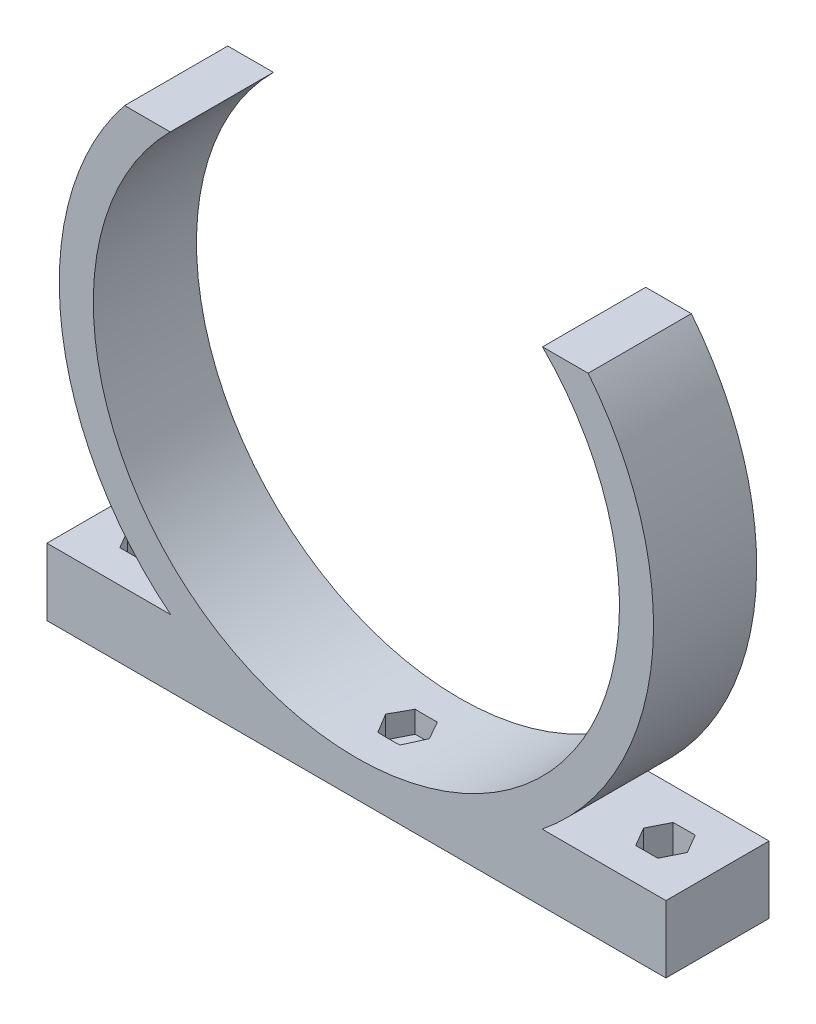
SolidWorks part; units mm, degrees
material "PE High Density"
ref_plane "Front Plane" through (0, 0, 0) normal (0, 0, 1) x (1, 0, 0)
ref_plane "Top Plane" through (0, 0, 0) normal (0, 1, 0) x (1, 0, 0)
ref_plane "Right Plane" through (0, 0, 0) normal (1, 0, 0) x (0, 0, -1)
sketch "Sketch2" plane through (0, 0, 0) normal (0, 0, 1) x (1, 0, 0)
  line L0 (0, 0) -> (38.1, 0)
  line L1 (0, 0) -> (-38.1, 0)
  line L2 (-38.1, 0) -> (-38.1, 8.255)
  line L3 (38.1, 0) -> (38.1, 8.255)
  line L4 (38.1, 8.255) -> (22.86, 8.255)
  line L5 (-38.1, 8.255) -> (-22.8663, 8.255)
  line L6 (-28.5349, 59.69) -> (-22.9171, 59.69)
  line L7 (22.9107, 59.69) -> (28.5286, 59.69)
  arc A2 (-28.5349, 59.69) -> (-22.8663, 8.255) centre (-0.0032, 36.8046) ccw
  arc A3 (-22.9171, 59.69) -> (22.9107, 59.69) centre (-0.0032, 36.8046) ccw
  arc A4 (22.86, 8.255) -> (28.5286, 59.69) centre (-0.0032, 36.8046) ccw
  point P10 (0, 0)
  dimension "D7" = 4.191
  dimension "D8" = 64.77
  dimension "D9" = 4.4196
  dimension "D1" = 38.1
  dimension "D2" = 38.1
  dimension "D3" = 8.255
  dimension "D4" = 8.255
  dimension "D5" = 15.24
  dimension "D10" = 59.69
extrude "Boss-Extrude1" add sketch "Sketch2" along normal blind 12.7
sketch "Sketch3" plane through (0, 0, 0) normal (0, -1, 0) x (1, 0, 0)
  line L0 (-38.1, 0) -> (38.1, 0) construction
  line L1 (-38.1, 12.7) -> (-38.1, 0) construction
  circle A0 centre (0, 6.35) radius 1.27
  circle A1 centre (31.75, 6.35) radius 1.27
  circle A2 centre (-31.75, 6.35) radius 1.27
  dimension "D1" = 2.54
  dimension "D2" = 6.35
  dimension "D3" = 38.1
  dimension "D4" = 2.54
  dimension "D5" = 31.75
  dimension "D6" = 2.54
  dimension "D7" = 31.75
extrude "Cut-Extrude1" cut sketch "Sketch3" against normal blind 12.7
sketch "Sketch4" plane through (0, 8.255, 0) normal (0, 1, 0) x (1, 0, 0)
  line L0 (-30.4159, -8.69) -> (-33.1293, -8.69)
  line L1 (-33.1293, -8.69) -> (-34.503, -6.35)
  line L2 (-34.503, -6.35) -> (-33.2834, -3.9261)
  line L3 (-33.2834, -3.9261) -> (-30.57, -3.9166)
  line L4 (-30.57, -3.9166) -> (-29.2051, -6.2617)
  line L5 (-29.2051, -6.2617) -> (-30.4159, -8.69)
  line L6 (-22.8663, -12.7) -> (-38.1, -12.7) construction
  point P2 (0, 0)
  point P7 (0, 0)
  point P8 (0, 0)
  dimension "D1" = 0.2
  dimension "D2" = 120
  dimension "D3" = 6.35
extrude "Cut-Extrude2" cut sketch "Sketch4" against normal blind 3.937
pattern_linear "LPattern1" count 3 spacing 31.75 along (1, 0, 0) of "Cut-Extrude2"
sketch "Sketch6" plane through (0, 4.318, 0) normal (0, 1, 0) x (1, 0, 0)
  line L0 (1.3341, -8.69) -> (-1.3793, -8.69) construction
  line L1 (-1.5334, -3.9261) -> (-2.753, -6.35) construction
  line L2 (-2.753, -6.35) -> (-1.3793, -8.69) construction
  line L3 (1.3341, -8.69) -> (2.5449, -6.2617) construction
  line L4 (1.18, -3.9166) -> (2.5449, -6.2617) construction
  line L5 (-1.5334, -3.9261) -> (1.18, -3.9166) construction
  line L6 (1.3341, -8.69) -> (-1.3793, -8.69)
  line L7 (-1.5334, -3.9261) -> (-2.753, -6.35)
  line L8 (-2.753, -6.35) -> (-1.3793, -8.69)
  line L9 (1.3341, -8.69) -> (2.5449, -6.2617)
  line L10 (1.18, -3.9166) -> (2.5449, -6.2617)
  line L11 (-1.5334, -3.9261) -> (1.18, -3.9166)
extrude "Cut-Extrude3" cut sketch "Sketch6" against normal blind 2.54
